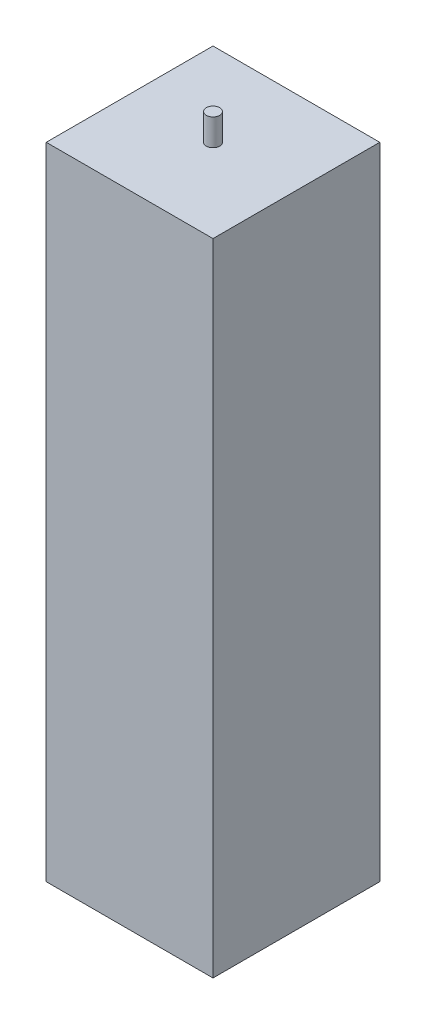
SolidWorks part; units mm, degrees
ref_plane "前视基准面" through (0, 0, 0) normal (0, 0, 1) x (1, 0, 0)
ref_plane "上视基准面" through (0, 0, 0) normal (0, 1, 0) x (1, 0, 0)
ref_plane "右视基准面" through (0, 0, 0) normal (1, 0, 0) x (0, 0, -1)
sketch "草图1" plane through (0, 0, 0) normal (0, 0, 1) x (1, 0, 0)
  line L0 (0, 69.3434) -> (0, -65.7797) construction
  line L1 (-6.25, 24) -> (6.25, 24)
  line L2 (-6.25, 24) -> (-6.25, -24)
  line L3 (-6.25, -24) -> (6.25, -24)
  line L4 (6.25, 24) -> (6.25, -24)
  line L5 (37.4584, 0) -> (-19.8575, 0) construction
  dimension "D1" = 48
  dimension "D2" = 12.5
extrude "凸台-拉伸1" add sketch "草图1" along normal blind 12.5
sketch "草图2" plane through (0, 24, 0) normal (0, 1, 0) x (1, 0, 0)
  line L0 (0, 2.6031) -> (0, -13.6541) construction
  line L1 (3.5518, -6.25) -> (-4.1173, -6.25) construction
  line L2 (6.25, 0) -> (-6.25, 0) construction
  line L3 (6.25, -12.5) -> (-6.25, -12.5) construction
  circle A0 centre (0, -6.25) radius 0.5
  dimension "D1" = 1
extrude "凸台-拉伸2" add sketch "草图2" along normal blind 2 and the other way blind 49.5
